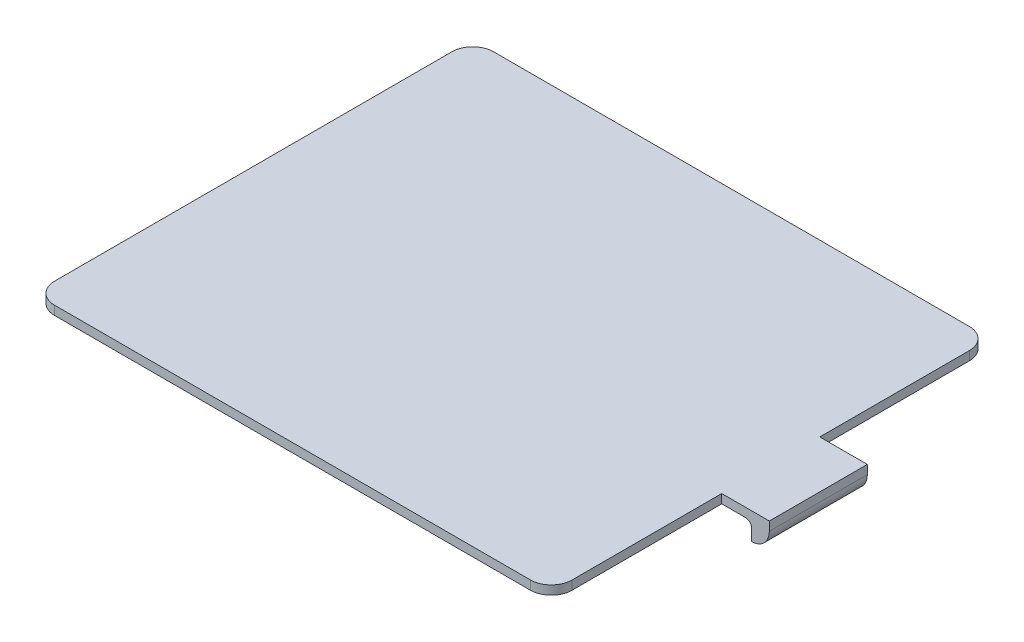
SolidWorks part; units mm, degrees
ref_plane "Front Plane" through (0, 0, 0) normal (0, 0, 1) x (1, 0, 0)
ref_plane "Top Plane" through (0, 0, 0) normal (0, 1, 0) x (1, 0, 0)
ref_plane "Right Plane" through (0, 0, 0) normal (1, 0, 0) x (0, 0, -1)
ref_plane "Plane1" through (0, -35, 0) normal (0, 1, 0) x (1, 0, 0)
sketch "Sketch2" plane through (0, -35, 0) normal (0, 1, 0) x (1, 0, 0)
  line L3 (21.3471, 31.0537) -> (101.4022, 31.0537)
  line L4 (17.8471, 27.5537) -> (17.8471, -39.2885)
  line L5 (21.3471, -42.7885) -> (101.4022, -42.7885)
  line L6 (104.9022, 27.5537) -> (104.9022, -39.2885)
  arc A5 (17.8471, 27.5537) -> (21.3471, 31.0537) centre (21.3471, 27.5537) cw
  arc A6 (17.8471, -39.2885) -> (21.3471, -42.7885) centre (21.3471, -39.2885) ccw
  arc A7 (101.4022, -42.7885) -> (104.9022, -39.2885) centre (101.4022, -39.2885) ccw
  arc A8 (104.9022, 27.5537) -> (101.4022, 31.0537) centre (101.4022, 27.5537) ccw
  point P14 (61.3747, -5.8674)
  dimension "D1" = 3.5
  dimension "D2" = 3.5
extrude "Boss-Extrude1" add sketch "Sketch2" against normal blind 1.5
sketch "Sketch3" plane through (104.9022, 0, 0) normal (1, 0, 0) x (0, 0, -1)
  line L0 (-39.2885, -35) -> (27.5537, -36.5) construction
  line L1 (-39.2885, -36.5) -> (27.5537, -35) construction
  line L2 (-39.2885, -36.5) -> (27.5537, -36.5) construction
  line L3 (-14.1117, -35) -> (2.3768, -35)
  line L4 (-14.1117, -35) -> (-14.1117, -36.5)
  line L5 (-14.1117, -36.5) -> (2.3768, -36.5)
  line L6 (2.3768, -35) -> (2.3768, -36.5)
  line L7 (-14.1117, -35) -> (2.3768, -36.5) construction
  line L8 (-14.1117, -36.5) -> (2.3768, -35) construction
  point P8 (-5.8674, -35.75)
extrude "Boss-Extrude2" add sketch "Sketch3" along normal blind 8
sketch "Sketch4" plane through (0, -36.5, 0) normal (0, -1, 0) x (-1, 0, 0)
  line L0 (-112.9022, 2.3768) -> (-104.9022, 2.3768) construction
  line L1 (-112.9022, -14.1117) -> (-109.9199, -14.1117)
  line L2 (-112.9022, -14.1117) -> (-112.9022, 2.3768)
  line L3 (-112.9022, 2.3768) -> (-109.9199, 2.3768)
  line L4 (-109.9199, -14.1117) -> (-109.9199, 2.3768)
revolve "Revolve1" add sketch "Sketch4" angle 90 about L4
fillet "Fillet1" radius 1 1 edges at (109.9199, -36.5, 5.8674)
